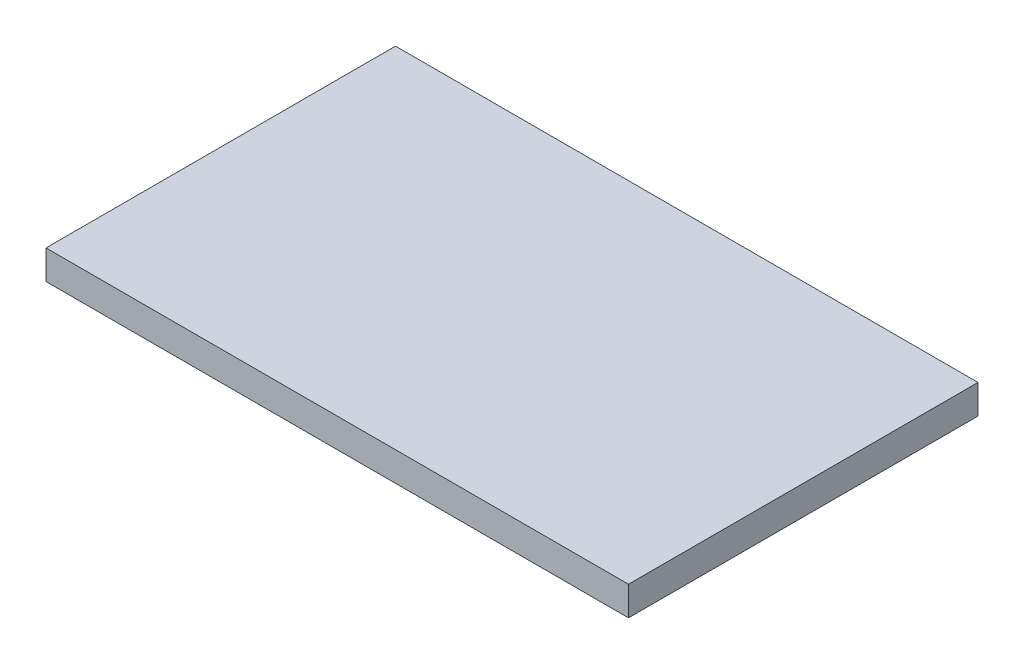
SolidWorks part; units mm, degrees
ref_plane "Front Plane" through (0, 0, 0) normal (0, 0, 1) x (1, 0, 0)
ref_plane "Top Plane" through (0, 0, 0) normal (0, 1, 0) x (1, 0, 0)
ref_plane "Right Plane" through (0, 0, 0) normal (1, 0, 0) x (0, 0, -1)
sketch "Sketch1" plane through (0, 0, 0) normal (0, 0, 1) x (1, 0, 0)
  line L0 (-88.9, 31.75) -> (-88.9, -31.75) construction
  line L1 (88.9, 38.1) -> (-38.1, 38.1)
  line L2 (88.9, 38.1) -> (88.9, 31.75)
  line L3 (88.9, 31.75) -> (-38.1, 31.75)
  line L4 (-38.1, 38.1) -> (-38.1, 31.75)
  dimension "D1" = 6.35
  dimension "D2" = 50.8
extrude "Boss-Extrude1" add sketch "Sketch1" along normal blind 76.2
